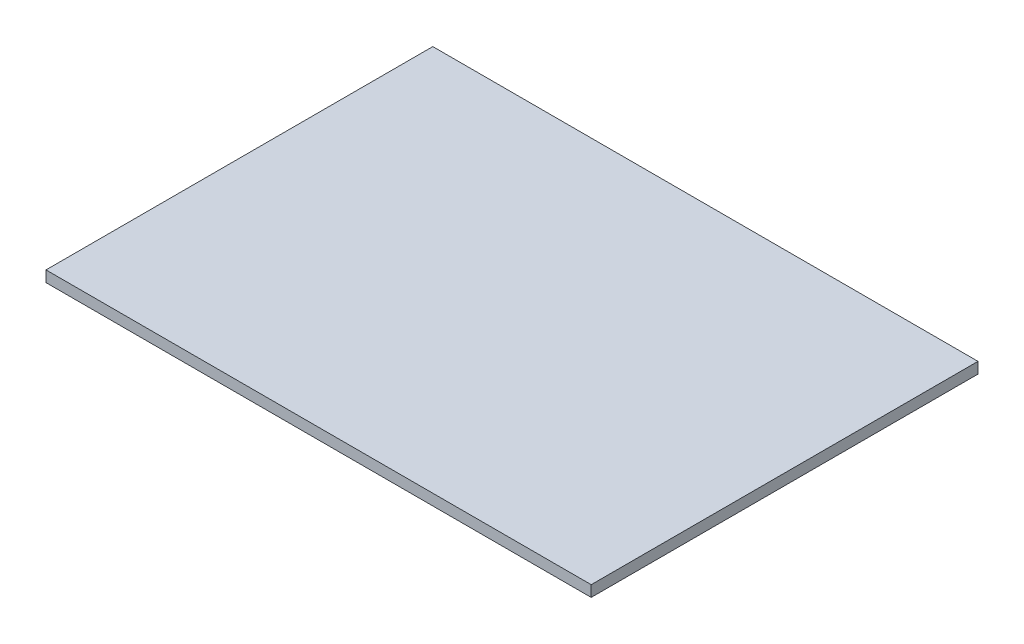
SolidWorks part; units mm, degrees
ref_plane "정면" through (0, 0, 0) normal (0, 0, 1) x (1, 0, 0)
ref_plane "윗면" through (0, 0, 0) normal (0, 1, 0) x (1, 0, 0)
ref_plane "우측면" through (0, 0, 0) normal (1, 0, 0) x (0, 0, -1)
sketch "스케치1" plane through (0, 0, 0) normal (0, 1, 0) x (1, 0, 0)
  line L1 (0, 0) -> (148, 0)
  line L2 (0, 0) -> (0, 105)
  line L3 (0, 105) -> (148, 105)
  line L4 (148, 0) -> (148, 105)
  dimension "D1" = 148
  dimension "D2" = 105
extrude "보스-돌출1" add sketch "스케치1" along normal blind 3
sketch "스케치2" plane through (0, 3, 0) normal (0, 1, 0) x (1, 0, 0)
  line L0 (74, 105) -> (74, 70) construction
  line L1 (148, 105) -> (0, 105) construction
  line L2 (74, 70) -> (74, 0) construction
  line L3 (0, 0) -> (148, 0) construction
  dimension "D1" = 70
